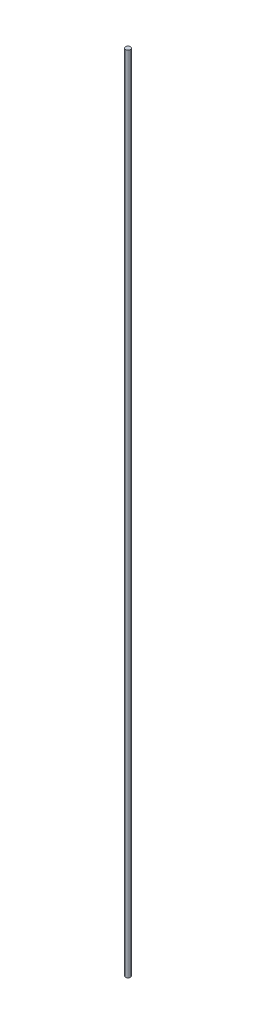
SolidWorks part; units mm, degrees
material "Thornel Mat VMA"
ref_plane "前视基准面" through (0, 0, 0) normal (0, 0, 1) x (1, 0, 0)
ref_plane "上视基准面" through (0, 0, 0) normal (0, 1, 0) x (1, 0, 0)
ref_plane "右视基准面" through (0, 0, 0) normal (1, 0, 0) x (0, 0, -1)
sketch "草图1" plane through (0, 0, 0) normal (0, 1, 0) x (1, 0, 0)
  circle A0 centre (0, 0) radius 0.5
  dimension "D1" = 1
extrude "凸台-拉伸1" add sketch "草图1" along normal blind 162
equation "\"m\"= 2"
